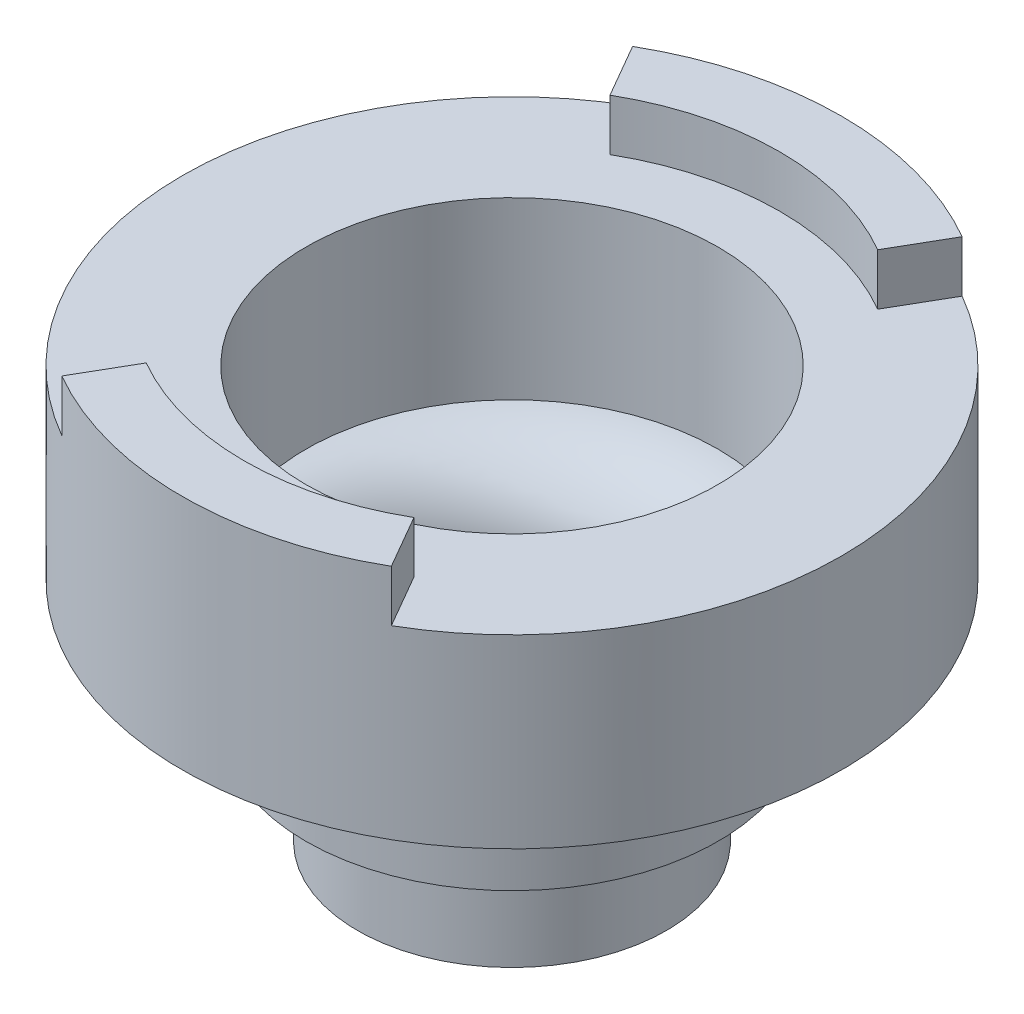
SolidWorks part; units mm, degrees
ref_plane "Front Plane" through (0, 0, 0) normal (1, 0, 0) x (0, 1, 0)
ref_plane "Top Plane" through (0, 0, 0) normal (0, 0, 1) x (0, 1, 0)
ref_plane "Right Plane" through (0, 0, 0) normal (0, 1, 0) x (-1, 0, 0)
sketch "Sketch3" plane through (0, 0, 0) normal (1, 0, 0) x (0, 1, 0)
  line L0 (0, -32) -> (0, 32)
  line L1 (-68.1198, 0) -> (68.1198, 0) construction
  line L2 (0, 32) -> (-18, 32)
  line L3 (-18, 32) -> (-18, -32)
  line L4 (-18, -32) -> (0, -32)
  line L5 (-18, 32) -> (-25, 20)
  line L6 (-25, 20) -> (-25, -20)
  line L7 (-25, -20) -> (-18, -32)
  line L8 (-25, 20) -> (-30, 20)
  line L9 (-30, 20) -> (-30, -20)
  line L10 (-30, -20) -> (-25, -20)
  line L11 (-30, 15) -> (-40, 15)
  line L12 (-40, 15) -> (-40, -15)
  line L13 (-40, -15) -> (-30, -15)
  point P4 (0, 0)
  point P7 (0, 0)
  dimension "D1" = 18
  dimension "D2" = 25
  dimension "D3" = 30
  dimension "D4" = 40
  dimension "D5" = 30
  dimension "D6" = 40
  dimension "D7" = 64
revolve "Revolve1" add sketch "Sketch3" angle 360 about L1
sketch "Sketch4" plane through (0, 0, 0) normal (0, 1, 0) x (-1, 0, 0)
  line L0 (24.9272, -43.1752) -> (-24.9272, 43.1752) construction
  line L1 (-24.9272, -43.1752) -> (24.9272, 43.1752) construction
  line L2 (0, -44.2718) -> (0, 44.2718) construction
  line L3 (-13, -22.5167) -> (-16, -27.7128)
  line L4 (16, -27.7128) -> (13, -22.5167)
  line L5 (-13, 22.5167) -> (-16, 27.7128)
  line L6 (16, 27.7128) -> (13, 22.5167)
  arc A0 (-13, 22.5167) -> (13, 22.5167) centre (0, 0) cw
  arc A1 (-13, -22.5167) -> (13, -22.5167) centre (0, 0) ccw
  circle A2 centre (0, 0) radius 32 construction
  arc A3 (-16, -27.7128) -> (16, -27.7128) centre (0, 0) ccw
  arc A4 (-16, 27.7128) -> (16, 27.7128) centre (0, 0) cw
  point P9 (0, 0)
  point P12 (0, 0)
  point P15 (0, 0)
  dimension "D1" = 52
  dimension "D2" = 60
extrude "Boss-Extrude2" add sketch "Sketch4" along normal blind 5
sketch "Sketch5" plane through (0, -40, 0) normal (0, -1, 0) x (1, 0, 0)
  circle A0 centre (0, 0) radius 8
  dimension "D1" = 16
extrude "Cut-Extrude1" cut sketch "Sketch5" against normal through all
sketch "Sketch6" plane through (0, 0, 0) normal (1, 0, 0) x (0, 1, 0)
  line L0 (-25, -20) -> (-25, 20) construction
  line L1 (0, -27.7128) -> (0, 27.7128) construction
  line L2 (0, 20) -> (-17, 20)
  line L3 (0, 20) -> (0, -20)
  line L4 (0, -20) -> (-17, -20)
  line L5 (-17, 20) -> (-17, -20)
  line L6 (48.1928, 0) -> (-48.1928, 0) construction
  line L7 (-25, 12) -> (-25, -12)
  arc A0 (-25, 12) -> (-17, 20) centre (-25, 20) ccw
  arc A1 (-25, -12) -> (-17, -20) centre (-25, -20) cw
  point P19 (0, 0)
  dimension "D1" = 8
  dimension "D3" = 40
revolve "Cut-Revolve1" cut sketch "Sketch6" angle 360 about L6
